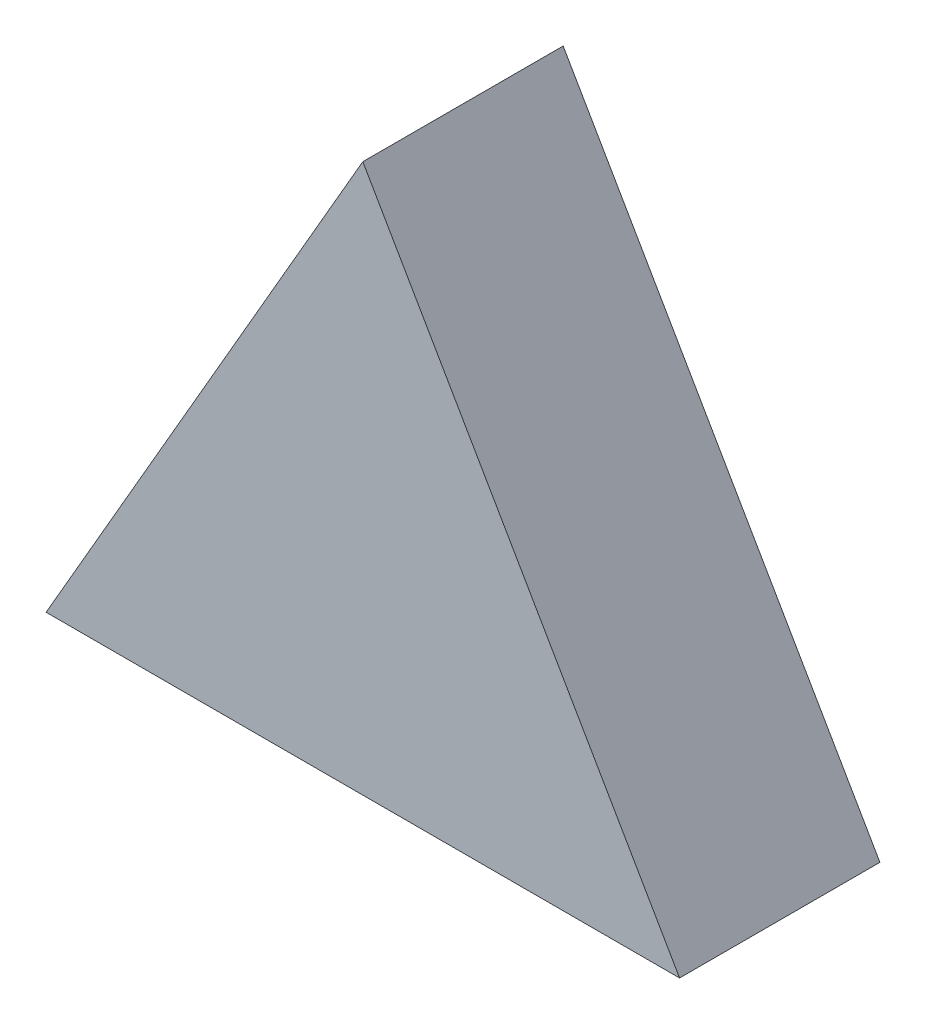
SolidWorks part; units mm, degrees
ref_plane "Front Plane" through (0, 0, 0) normal (0, 0, 1) x (1, 0, 0)
ref_plane "Top Plane" through (0, 0, 0) normal (0, 1, 0) x (1, 0, 0)
ref_plane "Right Plane" through (0, 0, 0) normal (1, 0, 0) x (0, 0, -1)
sketch "Sketch1" plane through (0, 0, 0) normal (0, 0, 1) x (1, 0, 0)
  line L0 (0, 0) -> (0, 117.3176) construction
  line L1 (0, 117.3176) -> (-101.6, -58.6588)
  line L2 (-101.6, -58.6588) -> (101.6, -58.6588)
  line L3 (101.6, -58.6588) -> (0, 117.3176)
  circle A0 centre (0, 0) radius 58.6588 construction
  dimension "D1" = 203.2
extrude "Boss-Extrude1" add sketch "Sketch1" along normal blind 64.262
